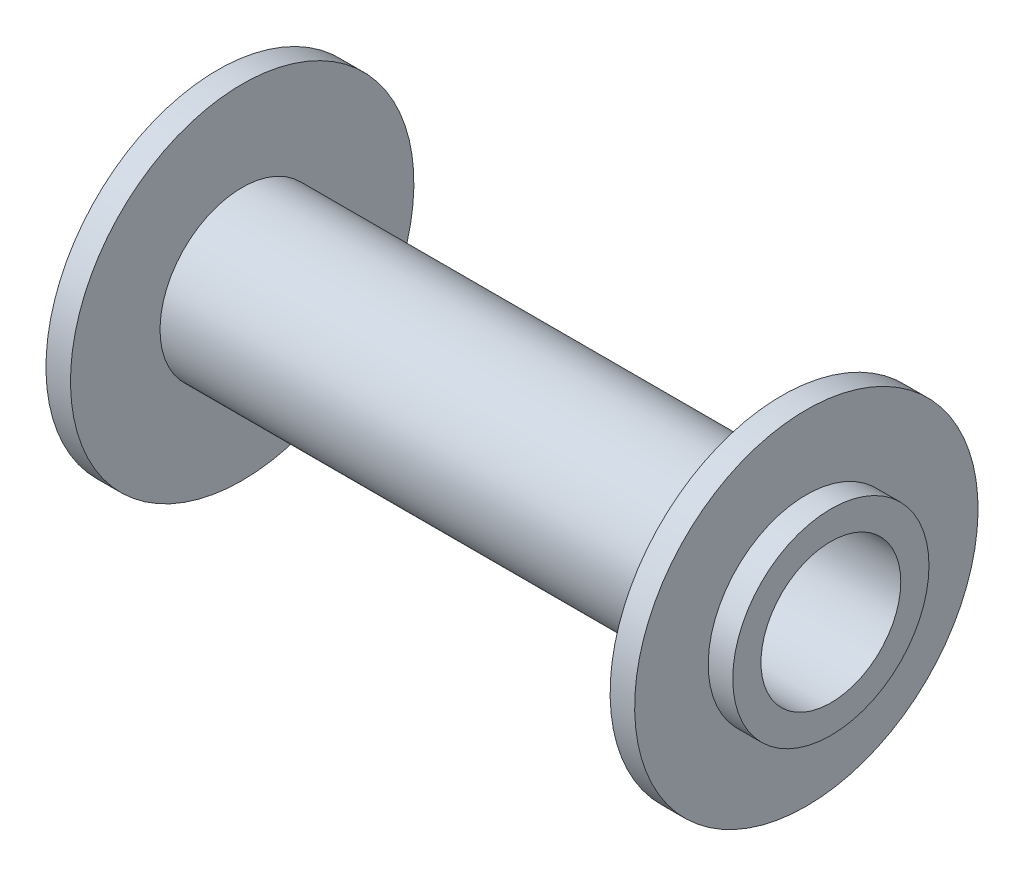
SolidWorks part; units mm, degrees
material "6061 Alloy"
ref_plane "Front Plane" through (0, 0, 0) normal (0, 0, 1) x (1, 0, 0)
ref_plane "Top Plane" through (0, 0, 0) normal (0, 1, 0) x (1, 0, 0)
ref_plane "Right Plane" through (0, 0, 0) normal (1, 0, 0) x (0, 0, -1)
sketch "Sketch1" plane through (0, 0, 0) normal (0, 0, 1) x (1, 0, 0)
  line L0 (-24, 0) -> (24, 0)
  line L1 (-24, 0) -> (-24, 14)
  line L2 (-24, 14) -> (-22, 14)
  line L3 (-22, 14) -> (-22, 6.7)
  line L4 (0, 17.4375) -> (0, -6.8117) construction
  line L5 (-22, 6.7) -> (22, 6.7)
  line L6 (22, 14) -> (22, 6.7)
  line L7 (24, 0) -> (24, 14)
  line L8 (24, 14) -> (22, 14)
  point P10 (0, 0)
  point P11 (0, 6.7)
  dimension "D1" = 48
  dimension "D2" = 6.7
  dimension "D3" = 14
revolve "Revolve1" add sketch "Sketch1" angle 360 about L0
sketch "Sketch2" plane through (24, 0, 0) normal (1, 0, 0) x (0, 0, -1)
  circle A0 centre (0, 0) radius 5.7
extrude "Cut-Extrude1" cut sketch "Sketch2" against normal through all
sketch "Sketch3" plane through (24, 0, 0) normal (1, 0, 0) x (0, 0, -1)
  circle A0 centre (0, 0) radius 5.7
  circle A1 centre (0, 0) radius 8
extrude "Boss-Extrude1" add sketch "Sketch3" along normal blind 2
sketch "Sketch4" plane through (-24, 0, 0) normal (-1, 0, 0) x (0, 0, 1)
  circle A0 centre (0, 0) radius 5.7
  circle A1 centre (0, 0) radius 8
extrude "Boss-Extrude2" add sketch "Sketch4" along normal blind 2
